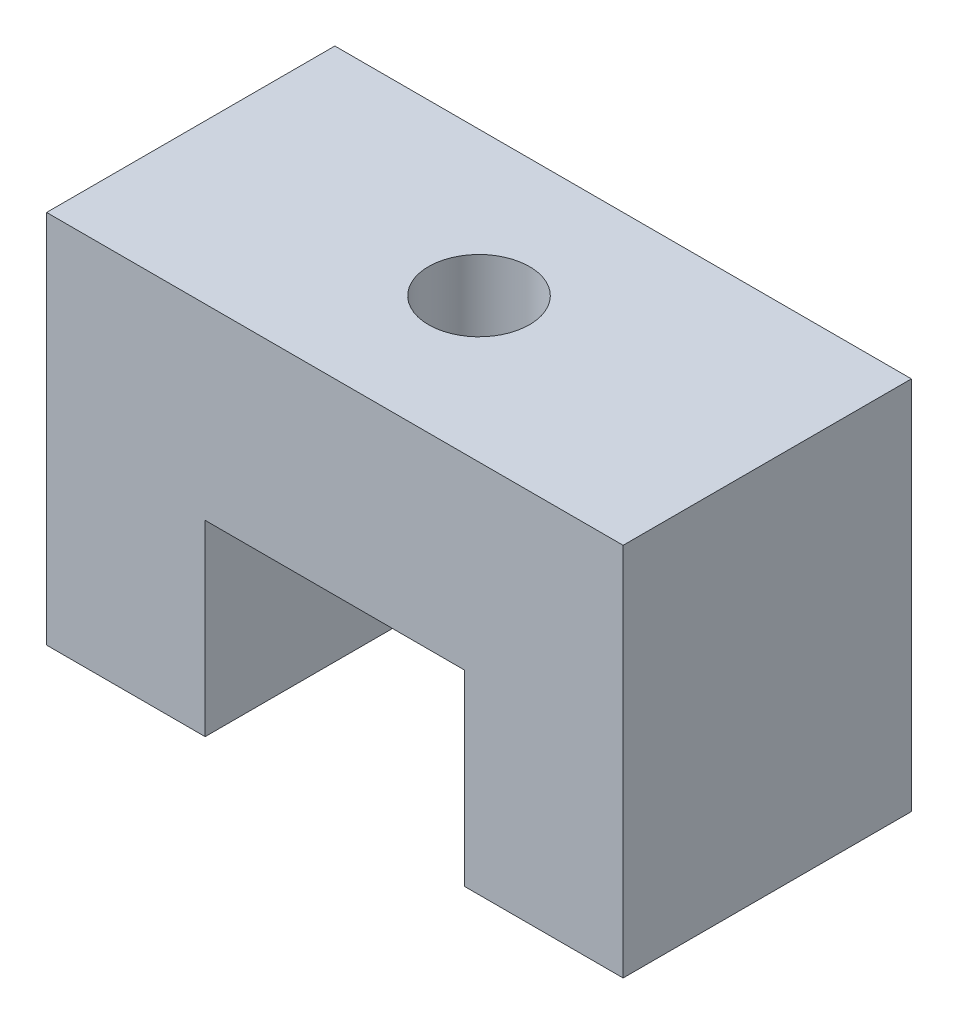
SolidWorks part; units mm, degrees
ref_plane "前视基准面" through (0, 0, 0) normal (0, 0, 1) x (1, 0, 0)
ref_plane "上视基准面" through (0, 0, 0) normal (0, 1, 0) x (1, 0, 0)
ref_plane "右视基准面" through (0, 0, 0) normal (1, 0, 0) x (0, 0, -1)
other "Configuration Table"
sketch "草图1" plane through (0, 0, 0) normal (0, 0, 1) x (1, 0, 0)
  line L0 (-10, 6.5) -> (10, 6.5)
  line L1 (-10, 6.5) -> (-10, -6.5)
  line L2 (10, 6.5) -> (10, -6.5)
  line L3 (-10, -6.5) -> (10, -6.5)
  line L4 (-10, 6.5) -> (10, -6.5) construction
  line L5 (10, 6.5) -> (-10, -6.5) construction
  line L6 (-4.5, 0) -> (4.5, 0)
  line L7 (-4.5, 0) -> (-4.5, -6.5)
  line L8 (4.5, 0) -> (4.5, -6.5)
  line L9 (-4.5, -6.5) -> (4.5, -6.5)
  line L10 (-4.5, 0) -> (4.5, -6.5) construction
  line L11 (4.5, 0) -> (-4.5, -6.5) construction
  point P1 (0, 0)
  point P2 (0, -3.25)
  dimension "D1" = 9
  dimension "D2" = 20
  dimension "D3" = 6.5
  dimension "D4" = 13
extrude "凸台-拉伸1" add sketch "草图1" along normal mid plane 10 contours L6 L8 L3 L2 L0 L1 L7
sketch "草图2" plane through (0, 6.5, 0) normal (0, 1, 0) x (1, 0, 0)
  circle A0 centre (0, 0) radius 1.75
  dimension "D1" = 3.5
extrude "切除-拉伸1" cut sketch "草图2" against normal through all both and the other way through all
